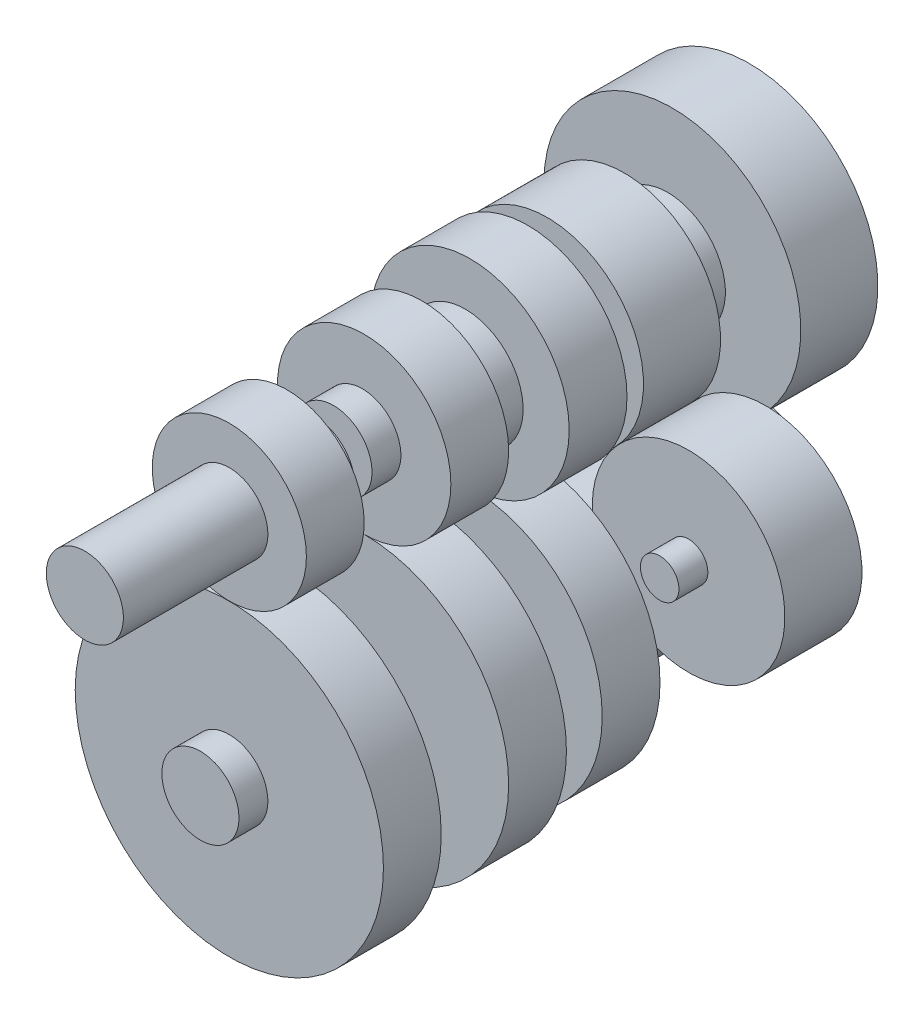
SolidWorks part; units mm, degrees
ref_plane "Front Plane" through (0, 0, 0) normal (0, 0, 1) x (1, 0, 0)
ref_plane "Top Plane" through (0, 0, 0) normal (0, 1, 0) x (1, 0, 0)
ref_plane "Right Plane" through (0, 0, 0) normal (1, 0, 0) x (0, 0, -1)
sketch "Sketch1" plane through (0, 0, 0) normal (0, 0, 1) x (1, 0, 0)
  circle A0 centre (0, 0) radius 101.6
  circle A1 centre (0, 152.4) radius 50.8
  dimension "D1" = 50.8
  dimension "D2" = 101.6
extrude "Boss-Extrude1" add sketch "Sketch1" against normal blind 38.1 contours A0 | A1
sketch "Sketch2" plane through (0, 0, -38.1) normal (0, 0, -1) x (-1, 0, 0)
  circle A0 centre (0, 0) radius 25.4
  dimension "D1" = 50.8
extrude "Boss-Extrude2" add sketch "Sketch2" along normal blind 50.8
sketch "Sketch3" plane through (0, 0, -88.9) normal (0, 0, -1) x (-1, 0, 0)
  circle A0 centre (0, 0) radius 95.25
  circle A1 centre (0, 152.4) radius 57.15
  circle M2 centre (0, 0) radius 25.4
  dimension "D1" = 95.25
  dimension "D2" = 57.15
extrude "Boss-Extrude4" add sketch "Sketch3" along normal blind 38.1 contours M2 | A0 M2 | A1
sketch "Sketch4" plane through (0, 0, -127) normal (0, 0, -1) x (-1, 0, 0)
  circle A0 centre (0, 0) radius 25.4
  circle A1 centre (0, 152.4) radius 25.4
  dimension "D1" = 50.8
  dimension "D2" = 50.8
extrude "Boss-Extrude5" add sketch "Sketch4" along normal blind 3.175 contours A1
sketch "Sketch5" plane through (0, 0, -130.175) normal (0, 0, -1) x (-1, 0, 0)
  circle A0 centre (0, 152.4) radius 38.1
  dimension "D1" = 76.2
extrude "Boss-Extrude6" add sketch "Sketch5" along normal blind 25.4
sketch "Sketch6" plane through (0, 0, -155.575) normal (0, 0, -1) x (-1, 0, 0)
  circle A0 centre (0, 152.4) radius 25.4
  dimension "D1" = 50.8
extrude "Boss-Extrude7" add sketch "Sketch6" along normal blind 3.175
sketch "Sketch7" plane through (0, 0, -127) normal (0, 0, -1) x (-1, 0, 0)
  circle A0 centre (0, 0) radius 25.4
  dimension "D1" = 50.8
extrude "Boss-Extrude8" add sketch "Sketch7" along normal blind 31.75
sketch "Sketch8" plane through (0, 0, -158.75) normal (0, 0, -1) x (-1, 0, 0)
  circle A0 centre (0, 0) radius 87.0857
  circle A1 centre (0, 152.4) radius 65.3143
  circle M1 centre (0, 0) radius 25.4
  dimension "D1" = 87.0857
  dimension "D2" = 65.3143
extrude "Boss-Extrude9" add sketch "Sketch8" along normal blind 38.1 contours A0 M1 | M1 | A1
sketch "Sketch9" plane through (0, 0, -196.85) normal (0, 0, -1) x (-1, 0, 0)
  circle A0 centre (0, 0) radius 25.4
  circle A1 centre (0, 152.4) radius 25.4
  dimension "D1" = 50.8
  dimension "D2" = 50.8
extrude "Boss-Extrude10" add sketch "Sketch9" along normal blind 12.7
sketch "Sketch10" plane through (0, 0, -209.55) normal (0, 0, -1) x (-1, 0, 0)
  circle A0 centre (0, 0) radius 50.8
  circle A1 centre (0, 152.4) radius 63.5
  circle A4 centre (-93.216, 66.1458) radius 63.5
  point P8 (-93.216, 66.1458)
  circle M6 centre (0, 0) radius 25.4
  dimension "D1" = 50.8
  dimension "D2" = 63.5
extrude "Boss-Extrude11" add sketch "Sketch10" along normal blind 50.8 contours A4 | A0 M6 | M6 | A1
sketch "Sketch11" plane through (0, 0, -260.35) normal (0, 0, -1) x (-1, 0, 0)
  circle A0 centre (0, 0) radius 25.4
  dimension "D1" = 50.8
extrude "Boss-Extrude12" add sketch "Sketch11" along normal blind 31.75
sketch "Sketch12" plane through (0, 0, -260.35) normal (0, 0, -1) x (-1, 0, 0)
  circle A0 centre (0, 152.4) radius 25.4
  dimension "D1" = 50.8
extrude "Boss-Extrude13" add sketch "Sketch12" along normal blind 3.175
sketch "Sketch13" plane through (0, 0, -263.525) normal (0, 0, -1) x (-1, 0, 0)
  circle A0 centre (0, 152.4) radius 38.1
  dimension "D1" = 76.2
extrude "Boss-Extrude14" add sketch "Sketch13" along normal blind 25.4
sketch "Sketch14" plane through (0, 0, -288.925) normal (0, 0, -1) x (-1, 0, 0)
  circle A0 centre (0, 152.4) radius 25.4
  dimension "D1" = 50.8
extrude "Boss-Extrude15" add sketch "Sketch14" along normal blind 3.175
sketch "Sketch15" plane through (0, 0, -292.1) normal (0, 0, -1) x (-1, 0, 0)
  circle A0 centre (0, 0) radius 50.8
  circle A1 centre (0, 152.4) radius 84.6667
  circle A4 centre (104.173, 47.037) radius 63.5
  point P8 (104.173, 47.037)
  circle M5 centre (0, 0) radius 25.4
  dimension "D1" = 50.8
  dimension "D2" = 84.6667
  dimension "D3" = 63.5
extrude "Boss-Extrude16" add sketch "Sketch15" along normal blind 50.8 contours A4 | A0 M5 | M5 | A1
sketch "Sketch16" plane through (0, 0, -209.55) normal (0, 0, 1) x (1, 0, 0)
  circle A0 centre (93.216, 66.1458) radius 12.7
  dimension "D1" = 25.4
extrude "Boss-Extrude17" add sketch "Sketch16" along normal blind 19.05
sketch "Sketch17" plane through (0, 0, -260.35) normal (0, 0, -1) x (-1, 0, 0)
  circle A0 centre (-93.216, 66.1458) radius 12.7
  dimension "D1" = 25.4
extrude "Boss-Extrude18" add sketch "Sketch17" along normal blind 19.05
sketch "Sketch18" plane through (0, 0, -342.9) normal (0, 0, -1) x (-1, 0, 0)
  circle A0 centre (0, 152.4) radius 25.4
  circle A1 centre (104.173, 47.037) radius 12.7
  circle A2 centre (0, 0) radius 25.4
  dimension "D1" = 50.8
  dimension "D2" = 25.4
  dimension "D3" = 50.8
extrude "Boss-Extrude19" add sketch "Sketch18" along normal blind 19.05
sketch "Sketch19" plane through (0, 0, -292.1) normal (0, 0, 1) x (1, 0, 0)
  circle A0 centre (-104.173, 47.037) radius 12.7
  dimension "D1" = 25.4
extrude "Boss-Extrude20" add sketch "Sketch19" along normal blind 50.8
sketch "Sketch20" plane through (0, 0, 0) normal (0, 0, 1) x (1, 0, 0)
  circle A0 centre (0, 0) radius 25.4
  circle A1 centre (0, 152.4) radius 25.4
  dimension "D1" = 50.8
  dimension "D2" = 50.8
extrude "Boss-Extrude21" add sketch "Sketch20" along normal blind 19.05
sketch "Sketch21" plane through (0, 0, -88.9) normal (0, 0, 1) x (1, 0, 0)
  circle A0 centre (-1.1872, 152.4) radius 25.4
  dimension "D1" = 50.8
extrude "Boss-Extrude22" add sketch "Sketch21" along normal blind 19.05
sketch "Sketch22" plane through (0, 0, -38.1) normal (0, 0, -1) x (-1, 0, 0)
  circle A0 centre (0, 152.4) radius 25.4
  dimension "D1" = 50.8
extrude "Boss-Extrude23" add sketch "Sketch22" along normal blind 19.05
sketch "Sketch23" plane through (0, 0, 19.05) normal (0, 0, 1) x (1, 0, 0)
sketch "Sketch24" plane through (0, 0, 19.05) normal (0, 0, 1) x (1, 0, 0)
  circle A1 centre (0, 152.4) radius 25.4
extrude "Boss-Extrude24" add sketch "Sketch24" along normal blind 76.2
